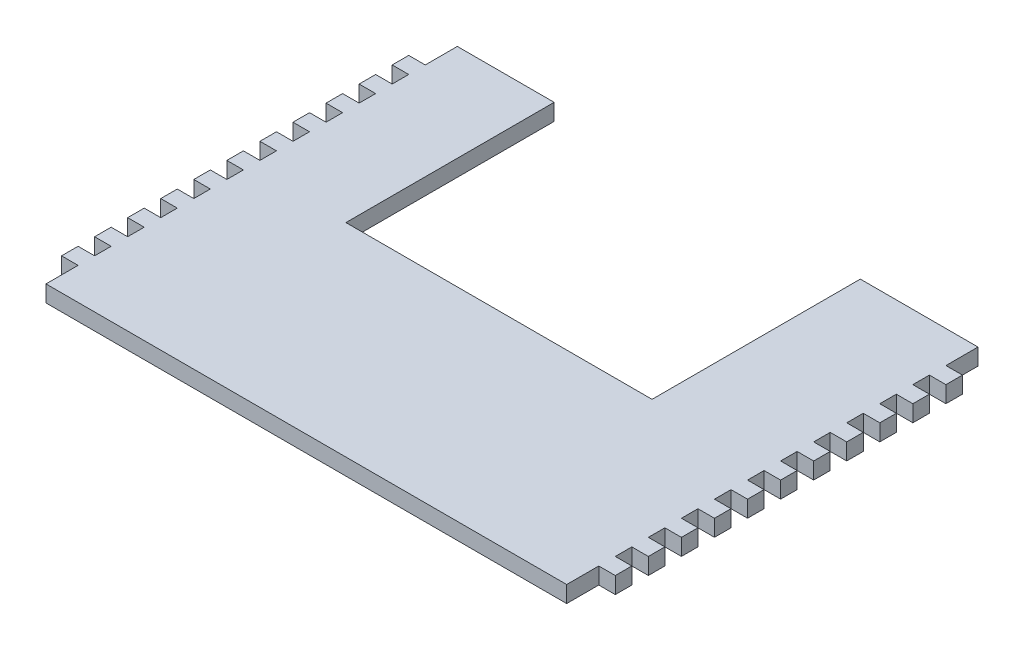
SolidWorks part; units mm, degrees
ref_plane "Front Plane" through (0, 0, 0) normal (0, 0, 1) x (1, 0, 0)
ref_plane "Top Plane" through (0, 0, 0) normal (0, 1, 0) x (1, 0, 0)
ref_plane "Right Plane" through (0, 0, 0) normal (1, 0, 0) x (0, 0, -1)
sketch "Sketch2" plane through (0, 0, 0) normal (0, 1, 0) x (1, 0, 0)
  line L1 (-4, -17) -> (96, -17) construction
  line L2 (-4, -17) -> (-4, 62) construction
  line L3 (-4, 62) -> (96, 62) construction
  line L4 (96, -17) -> (96, 62) construction
  circle A0 centre (0, 0) radius 1.38 construction
  circle A1 centre (0, 58) radius 1.38 construction
  circle A2 centre (86, 58) radius 1.38 construction
  circle A3 centre (86, 0) radius 1.38 construction
  dimension "D5" = 2.76
  dimension "D1" = 100
  dimension "D2" = 79
  dimension "D3" = 4
  dimension "D4" = 17
  dimension "D6" = 4
  dimension "D7" = 4
  dimension "D8" = 4
  dimension "D9" = 10
  dimension "D10" = 10
  dimension "D11" = 17
sketch "Sketch3" plane through (0, 0, 0) normal (0, 1, 0) x (1, 0, 0)
  line L1 (-4, 62) -> (96, 62)
  line L2 (-4, 62) -> (-4, -17)
  line L3 (-4, -17) -> (96, -17)
  line L4 (96, 62) -> (96, -17)
extrude "Boss-Extrude1" add sketch "Sketch3" along normal blind 3.175
sketch "Sketch4" plane through (0, 3.175, 0) normal (0, 1, 0) x (1, 0, 0)
  circle A0 centre (0, 58) radius 1.38
  circle A1 centre (86, 58) radius 1.38
  circle A2 centre (86, 0) radius 1.38
  circle A3 centre (0, 0) radius 1.38
  dimension "D1" = 2.76
extrude "Cut-Extrude1" [suppressed] cut sketch "Sketch4" against normal blind 3.175
sketch "Sketch5" plane through (0, 3.175, 0) normal (0, 1, 0) x (1, 0, 0)
  line L0 (-4, 62) -> (96, 62) construction
  line L1 (14.6, 62) -> (73.4, 62)
  line L2 (14.6, 62) -> (14.6, 22)
  line L3 (14.6, 22) -> (73.4, 22)
  line L4 (73.4, 62) -> (73.4, 22)
  dimension "D1" = 14.6
  dimension "D2" = 40
  dimension "D3" = 58.8
extrude "Cut-Extrude2" cut sketch "Sketch5" against normal blind 3.175
sketch "Sketch8" plane through (96, 0, 0) normal (1, 0, 0) x (0, 0, -1)
  line L1 (-17, 3.175) -> (62, 3.175)
  line L2 (-17, 3.175) -> (-17, 0)
  line L3 (-17, 0) -> (62, 0)
  line L4 (62, 3.175) -> (62, 0)
sketch "Sketch9" plane through (-4, 0, 0) normal (-1, 0, 0) x (0, 0, 1)
  line L0 (17, 0) -> (-62, 0) construction
  line L1 (-62, 3.175) -> (17, 3.175)
  line L2 (-62, 3.175) -> (-62, 0)
  line L3 (-62, 0) -> (17, 0)
  line L4 (17, 3.175) -> (17, 0)
ref_plane "Plane3" through (46, 0, 0) normal (-1, 0, 0) x (0, 0, 1)
ref_plane "Plane4" through (0, 0, -22.5) normal (0, 0, -1) x (-1, 0, 0)
sketch "Sketch11" plane through (0, 3.175, 0) normal (0, 1, 0) x (1, 0, 0)
  line L0 (-4, -17) -> (-4, 62) construction
  line L1 (-0.825, 20.9125) -> (-7.175, 20.9125)
  line L2 (-0.825, 20.9125) -> (-0.825, 24.0875)
  line L3 (-0.825, 24.0875) -> (-7.175, 24.0875)
  line L4 (-7.175, 20.9125) -> (-7.175, 24.0875)
  line L5 (-0.825, 20.9125) -> (-7.175, 24.0875) construction
  line L6 (-0.825, 24.0875) -> (-7.175, 20.9125) construction
  point P0 (-4, 22.5)
  dimension "D1" = 6.35
  dimension "D2" = 3.175
extrude "Boss-Extrude2" add sketch "Sketch11" against normal up to surface (3.175 mm away) up to face at (45, 0, -32.25)
mirror "Mirror2" about plane through (46, 0, 0) normal (-1, 0, 0) of "Boss-Extrude2"
pattern_linear "LPattern2" count 6 spacing 6.35 along (0, 0, -1) count 6 spacing 6.35 along (0, 0, 1) of "Mirror2", "Boss-Extrude2"
sketch "Sketch12" plane through (0, 3.175, 0) normal (0, 1, 0) x (1, 0, 0)
  circle A0 centre (0, 58) radius 3
  circle A1 centre (0, 0) radius 3
  circle A2 centre (86, 58) radius 3
  circle A3 centre (86, 0) radius 3
  dimension "D1" = 6
extrude "Cut-Extrude3" [suppressed] cut sketch "Sketch12" against normal up to next
sketch "Sketch13" plane through (0, 3.175, 0) normal (0, 1, 0) x (1, 0, 0)
  line L1 (-7.175, 62) -> (-19.525, 62)
  line L2 (-7.175, 62) -> (-7.175, -17)
  line L3 (-7.175, -17) -> (-19.525, -17)
  line L4 (-19.525, 62) -> (-19.525, -17)
  line L6 (-7.175, 30.4375) -> (-7.175, 27.2625) construction
  dimension "D1" = 12.35
extrude "Boss-Extrude4" add sketch "Sketch13" against normal up to surface (3.175 mm away) up to face at (45.9167, 0, -23.3125)
sketch "Sketch14" plane through (0, 3.175, 0) normal (0, 1, 0) x (1, 0, 0)
  line L1 (99.175, 62) -> (111.525, 62)
  line L2 (99.175, 62) -> (99.175, -17)
  line L3 (99.175, -17) -> (111.525, -17)
  line L4 (111.525, 62) -> (111.525, -17)
  dimension "D1" = 12.35
extrude "Boss-Extrude5" add sketch "Sketch14" against normal up to surface (3.175 mm away) up to face at (-5.5875, 0, -25.675)
sketch "Sketch15" plane through (0, 3.175, 0) normal (0, 1, 0) x (1, 0, 0)
  line L0 (-13.35, 73.46) -> (-13.35, -30.7789) construction
  line L1 (-19.525, 62) -> (-19.525, -17) construction
  line L2 (-7.175, 62) -> (-19.525, 62) construction
  circle A0 centre (-13.35, 54) radius 1.5
  circle A1 centre (-13.35, -9) radius 1.5
  dimension "D2" = 3
  dimension "D3" = 3
  dimension "D1" = 6.175
  dimension "D4" = 63
  dimension "D5" = 8
sketch "Sketch16" plane through (0, 3.175, 0) normal (0, 1, 0) x (1, 0, 0)
  line L0 (105.35, 68.5201) -> (105.35, 28.0125) construction
  line L1 (111.525, -17) -> (111.525, 62) construction
  line L2 (111.525, 62) -> (99.175, 62) construction
  line L3 (99.175, -17) -> (111.525, -17) construction
  circle A0 centre (105.35, 54) radius 1.5
  circle A1 centre (105.35, -9) radius 1.5
  dimension "D4" = 3
  dimension "D5" = 3
  dimension "D1" = 6.175
  dimension "D2" = 8
  dimension "D3" = 8
extrude "Cut-Extrude4" cut sketch "Sketch15" against normal blind 10
extrude "Cut-Extrude5" cut sketch "Sketch16" against normal blind 10
sketch "Sketch17" plane through (0, 3.175, 0) normal (0, 1, 0) x (1, 0, 0)
  line L1 (-19.525, 62) -> (-7.175, 62)
  line L2 (-19.525, 62) -> (-19.525, -17)
  line L3 (-19.525, -17) -> (-7.175, -17)
  line L4 (-7.175, 62) -> (-7.175, -17)
  line L5 (111.525, 62) -> (99.175, 62)
  line L6 (111.525, 62) -> (111.525, -17)
  line L7 (111.525, -17) -> (99.175, -17)
  line L8 (99.175, 62) -> (99.175, -17)
extrude "Cut-Extrude6" cut sketch "Sketch17" against normal blind 10
